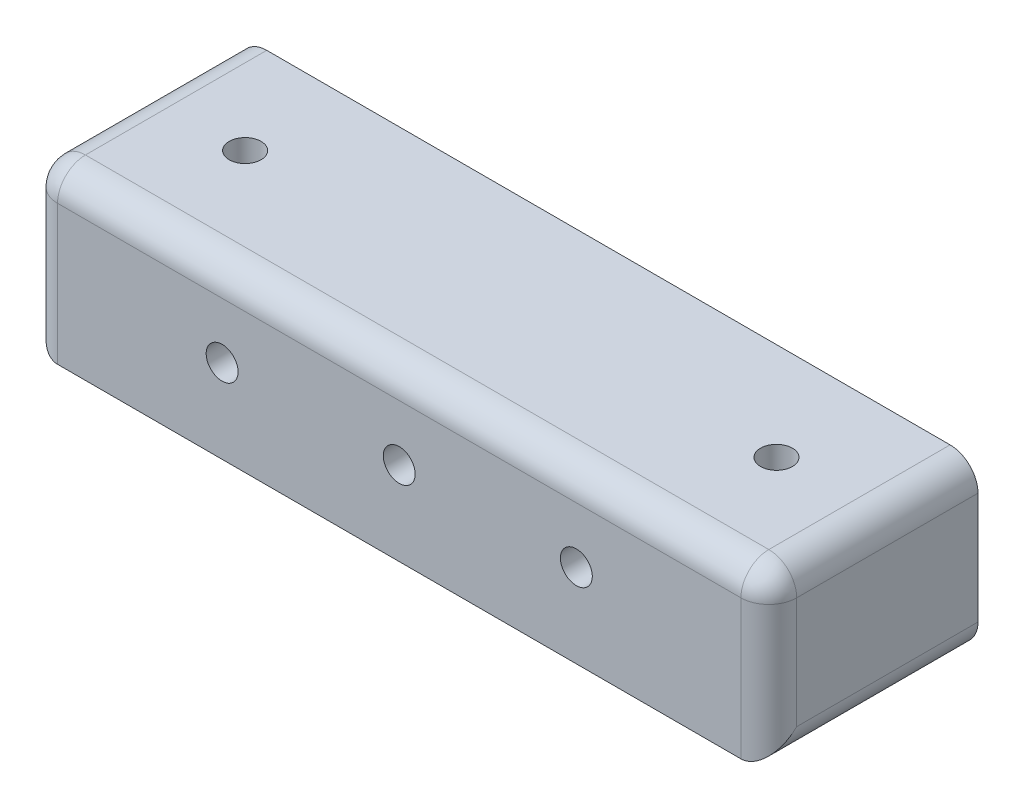
SolidWorks part; units mm, degrees
ref_plane "Front Plane" through (0, 0, 0) normal (0, 0, 1) x (1, 0, 0)
ref_plane "Top Plane" through (0, 0, 0) normal (0, 1, 0) x (1, 0, 0)
ref_plane "Right Plane" through (0, 0, 0) normal (1, 0, 0) x (0, 0, -1)
sketch "Sketch1" plane through (0, 0, 0) normal (0, 0, 1) x (1, 0, 0)
  line L1 (-26.5, 6) -> (26.5, 6)
  line L2 (-26.5, 6) -> (-26.5, -6)
  line L3 (-26.5, -6) -> (26.5, -6)
  line L4 (26.5, 6) -> (26.5, -6)
  line L5 (-26.5, 6) -> (26.5, -6) construction
  line L6 (-26.5, -6) -> (26.5, 6) construction
  point P0 (0, 0)
  dimension "D1" = 12
  dimension "D2" = 53
extrude "Boss-Extrude1" add sketch "Sketch1" along normal blind 15
sketch "Sketch2" plane through (0, -6, 0) normal (0, -1, 0) x (1, 0, 0)
  line L0 (0, 0) -> (0, 15) construction
  line L1 (-26.5, 0) -> (26.5, 0) construction
  line L2 (-26.5, 15) -> (26.5, 15) construction
  line L3 (-19.05, 7) -> (19.05, 7) construction
  circle A0 centre (-19.05, 7) radius 1.143
  circle A1 centre (19.05, 7) radius 1.143
  point P8 (0, 7)
  dimension "D1" = 2.286
  dimension "D2" = 38.1
  dimension "D3" = 8
extrude "Cut-Extrude1" cut sketch "Sketch2" against normal up to next
fillet "Fillet1" radius 2 7 edges at (26.5, 0, 15) (0, 6, 15) (-26.5, 0, 15) (-26.5, 6, 7.5) (26.5, 6, 7.5) (26.5, -6, 7.5) (-26.5, -6, 7.5)
sketch "Sketch3" plane through (0, 0, 0) normal (0, 0, -1) x (-1, 0, 0)
  line L0 (0, 6) -> (0, -6) construction
  line L1 (-24.5, 6) -> (24.5, 6) construction
  line L2 (24.5, -6) -> (-24.5, -6) construction
  line L3 (-26.5, 0) -> (26.5, 0) construction
  line L4 (26.5, 4) -> (26.5, -4) construction
  circle A0 centre (-12.7, 0) radius 1.143
  circle A1 centre (12.7, 0) radius 1.143
  circle A2 centre (0, 0) radius 1.143
  point P12 (0, 0)
  dimension "D1" = 2.286
  dimension "D2" = 25.4
  dimension "D3" = 12.7
extrude "Cut-Extrude2" cut sketch "Sketch3" against normal through all
